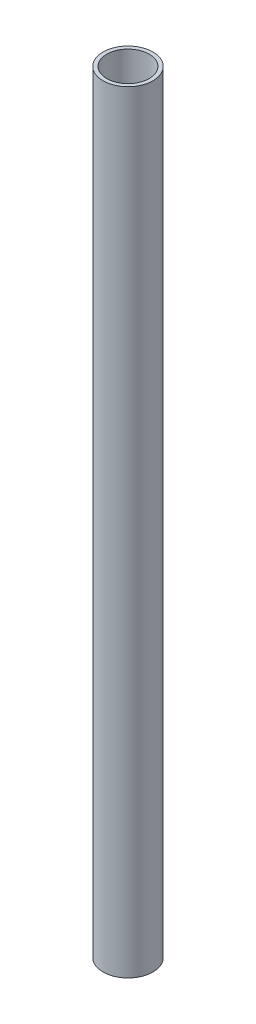
SolidWorks part; units mm, degrees
material "PVC Rigid"
ref_plane "Front Plane" through (0, 0, 0) normal (0, 0, 1) x (1, 0, 0)
ref_plane "Top Plane" through (0, 0, 0) normal (0, 1, 0) x (1, 0, 0)
ref_plane "Right Plane" through (0, 0, 0) normal (1, 0, 0) x (0, 0, -1)
sketch "Sketch1" plane through (0, 0, 0) normal (0, 1, 0) x (1, 0, 0)
  circle A0 centre (0, 0) radius 20
  circle A1 centre (0, 0) radius 17
  dimension "D1" = 40
  dimension "D2" = 3
extrude "Boss-Extrude1" add sketch "Sketch1" along normal blind 619
